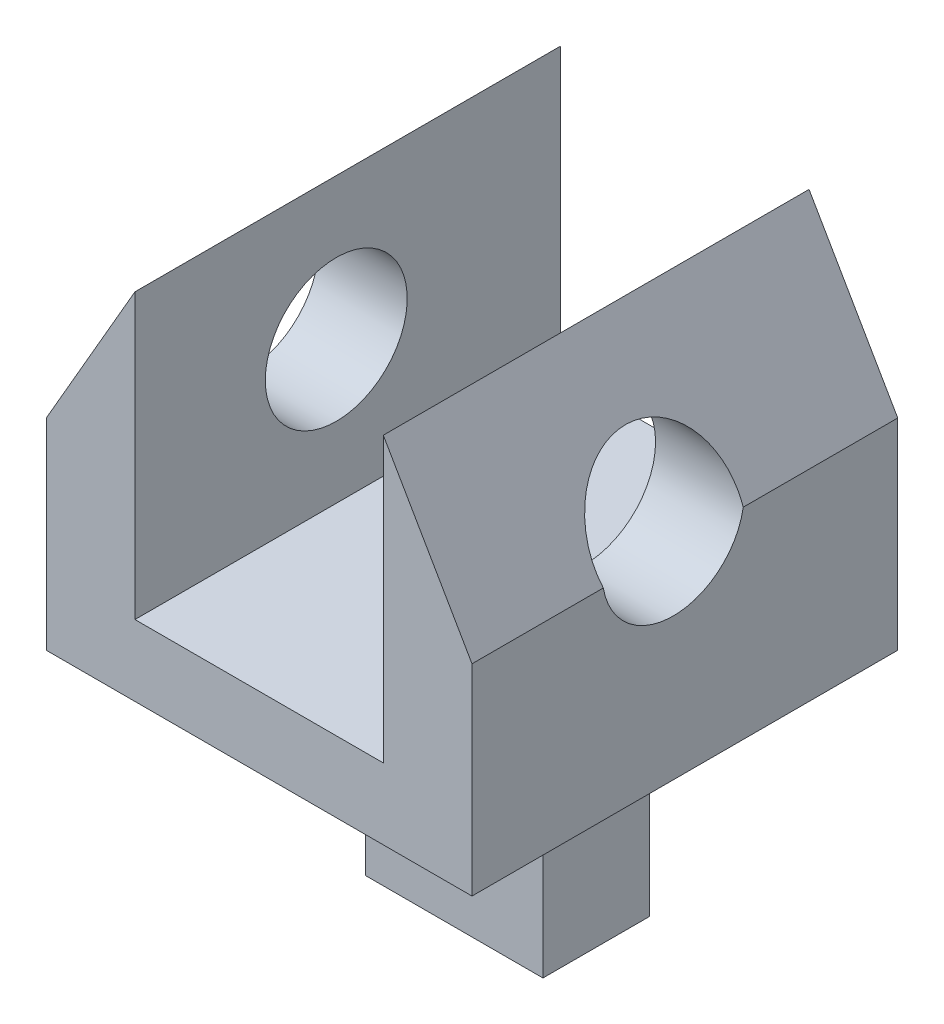
SolidWorks part; units mm, degrees
ref_plane "Front Plane" through (0, 0, 0) normal (0, 0, 1) x (1, 0, 0)
ref_plane "Top Plane" through (0, 0, 0) normal (0, 1, 0) x (1, 0, 0)
ref_plane "Right Plane" through (0, 0, 0) normal (1, 0, 0) x (0, 0, -1)
sketch "Sketch1" plane through (0, 0, 0) normal (0, 1, 0) x (1, 0, 0)
  line L1 (-6, -6) -> (6, -6)
  line L2 (-6, -6) -> (-6, 6)
  line L3 (-6, 6) -> (6, 6)
  line L4 (6, -6) -> (6, 6)
  line L5 (-6, -6) -> (6, 6) construction
  line L6 (-6, 6) -> (6, -6) construction
  point P0 (0, 0)
  dimension "D1" = 12
  dimension "D2" = 12
extrude "Boss-Extrude1" add sketch "Sketch1" along normal blind 2
sketch "Sketch2" plane through (0, 2, 0) normal (0, 1, 0) x (1, 0, 0)
  line L0 (-6, -6) -> (6, -6) construction
  line L1 (-6, 6) -> (-3.5, 6)
  line L2 (-6, 6) -> (-6, -6)
  line L3 (-6, -6) -> (-3.5, -6)
  line L4 (-3.5, 6) -> (-3.5, -6)
  line L5 (6, 6) -> (-6, 6) construction
  line L6 (6, -6) -> (3.5, -6)
  line L7 (6, -6) -> (6, 6)
  line L8 (6, 6) -> (3.5, 6)
  line L9 (3.5, -6) -> (3.5, 6)
  line L10 (-3.5, 6) -> (3.5, 6) construction
  line L11 (-6, 6) -> (6, 6) construction
  point P16 (0, 6)
  point P17 (0, 6)
  dimension "D1" = 7
extrude "Boss-Extrude2" add sketch "Sketch2" along normal blind 8
sketch "Sketch4" plane through (3.5, 0, 0) normal (-1, 0, 0) x (0, 0, 1)
  line L0 (-6, 2) -> (6, 2) construction
  circle A0 centre (0.3261, 6) radius 2
  dimension "D1" = 4
  dimension "D2" = 4
sketch "Sketch5" plane through (0, 0, 6) normal (0, 0, 1) x (1, 0, 0)
  line L0 (-3.5, 10) -> (-6, 5.6699)
  line L1 (-3.5, 10) -> (-3.5, 2) construction
  line L2 (-6, 10) -> (-6, 0) construction
  line L3 (0, 0) -> (0, 10.4395) construction
  line L4 (3.5, 10) -> (6, 5.6699)
  line L5 (3.5, 10) -> (3.5, 2) construction
  line L6 (6, 10) -> (6, 0) construction
  line L7 (3.5, 10) -> (6, 10)
  line L8 (6, 10) -> (6, 5.6699)
  line L9 (-6, 10) -> (-6, 5.6699)
  line L10 (-3.5, 10) -> (-6, 10)
  dimension "D1" = 30
  dimension "D2" = 30
extrude "Cut-Extrude1" cut sketch "Sketch5" against normal through all
extrude "Cut-Extrude2" cut sketch "Sketch4" against normal through all and the other way through all
sketch "Sketch6" plane through (0, 0, 0) normal (0, -1, 0) x (1, 0, 0)
  line L1 (-6, -6) -> (-1, -6)
  line L2 (-6, -6) -> (-6, -3)
  line L3 (-6, -3) -> (-1, -3)
  line L4 (-1, -6) -> (-1, -3)
  dimension "D1" = 5
  dimension "D2" = 3
extrude "Boss-Extrude3" add sketch "Sketch6" along normal blind 10
ref_point "Point1"
hole_wizard "Ø3.0mm Dowel Hole1" positions "Sketch7" profile "Sketch8" hole size "Ø3.0" standard "ANSI Metric"
sketch "Sketch7" plane through (0, 0, -3) normal (0, 0, 1) x (1, 0, 0)
  point P0 (-3.5, -5)
sketch "Sketch8" plane through (-3.5, -5, -3) normal (1, 0, 0) x (0, -1, 0)
  line L0 (0, 0) -> (0, 3.9013)
  line L1 (0, 3.9013) -> (1.5, 3)
  line L2 (1.5, 3) -> (1.5, 0)
  line L5 (1.5, 0) -> (0, 0)
  line L10 (0, 3.9013) -> (-1.5, 3) construction
  line L11 (0, -6.35) -> (0, 107.95) construction
  dimension "Hole Dia." = 3
  dimension "Hole Depth" = 3
  dimension "Drill Angle" = 118
